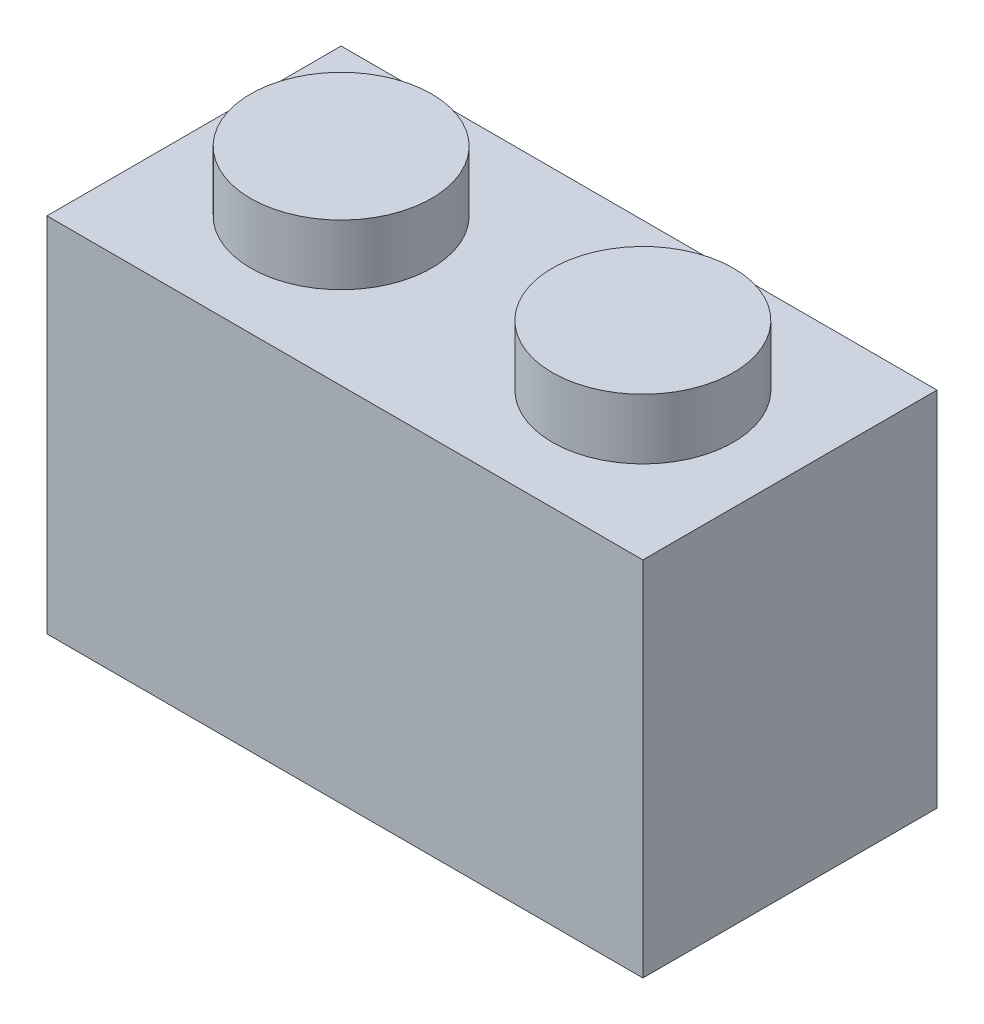
SolidWorks part; units mm, degrees
material "ABS"
ref_plane "Front Plane" through (0, 0, 0) normal (0, 0, 1) x (1, 0, 0)
ref_plane "Top Plane" through (0, 0, 0) normal (0, 1, 0) x (1, 0, 0)
ref_plane "Right Plane" through (0, 0, 0) normal (1, 0, 0) x (0, 0, -1)
sketch "Sketch1" plane through (0, 0, 0) normal (0, 0, 1) x (1, 0, 0)
  line L1 (0, 0) -> (15.8, 0)
  line L2 (0, 0) -> (0, 9.6)
  line L3 (0, 9.6) -> (15.8, 9.6)
  line L4 (15.8, 0) -> (15.8, 9.6)
  dimension "D1" = 15.8
  dimension "D2" = 9.6
extrude "Boss-Extrude1" add sketch "Sketch1" against normal blind 7.8 contours L2 L1 L4 L3
sketch "Sketch2" plane through (0, 9.6, 0) normal (0, 1, 0) x (1, 0, 0)
  line L0 (0, 0) -> (15.8, 0) construction
  line L1 (0, 7.8) -> (0, 0) construction
  circle A0 centre (3.9, 3.9) radius 2.4
  dimension "D1" = 4.8
  dimension "D2" = 3.9
  dimension "D3" = 3.9
extrude "Boss-Extrude2" add sketch "Sketch2" along normal blind 1.6 contours A0
pattern_linear "LPattern1" count 2 spacing 8 along (1, 0, 0) count 2 spacing 8 along (0, 0, 1) of "Boss-Extrude2"
shell "Shell1" thickness 1.2
sketch "Sketch3" plane through (0, 8.4, 0) normal (0, -1, 0) x (1, 0, 0)
  line L0 (0, 0) -> (15.8, 0) construction
  line L1 (0, -7.8) -> (0, 0) construction
  circle A0 centre (7.9, -3.9) radius 1.5
  dimension "D1" = 3
  dimension "D2" = 3.9
  dimension "D3" = 7.9
extrude "Boss-Extrude3" add sketch "Sketch3" along normal offset from surface (8.2 mm away) 0.2 up to face at (7.9, 0, -3.9)
